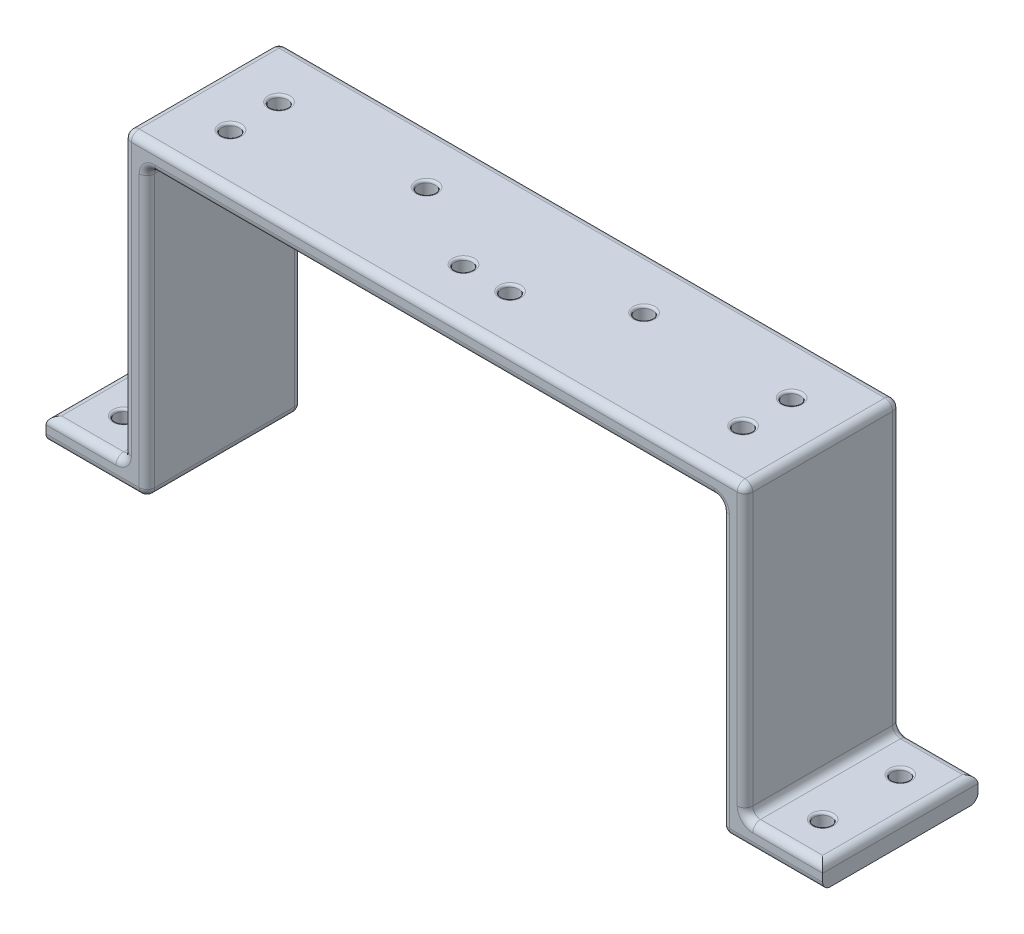
SolidWorks part; units mm, degrees
ref_plane "前视基准面" through (0, 0, 0) normal (0, 0, 1) x (1, 0, 0)
ref_plane "上视基准面" through (0, 0, 0) normal (0, 1, 0) x (1, 0, 0)
ref_plane "右视基准面" through (0, 0, 0) normal (1, 0, 0) x (0, 0, -1)
other "Configuration Table"
sketch "草图1" plane through (0, 0, 0) normal (0, 1, 0) x (1, 0, 0)
  line L0 (0, -55) -> (0, 55) construction
  line L1 (-5, 10) -> (5, 10)
  line L2 (-5, 10) -> (-5, -10)
  line L3 (-5, -10) -> (5, -10)
  line L4 (5, 10) -> (5, -10)
  line L5 (-55, 0) -> (55, 0) construction
  dimension "D1" = 20
  dimension "D2" = 10
  dimension "D3" = 5
  dimension "D4" = 10
extrude "凸台-拉伸1" add sketch "草图1" along normal blind 3
hole_wizard "Ø2.2 (2.2) Diameter Hole2" positions "草图2" profile "草图3" hole size "Ø2.2" standard "ANSI Metric" end condition up to next
sketch "草图2" plane through (0, 3, 0) normal (0, 1, 0) x (1, 0, 0)
  line L0 (0, -1.65) -> (0, 1.65) construction
  line L1 (5, 10) -> (-5, 10) construction
  point P0 (0, 5)
  point P4 (0, -5)
  dimension "D1" = 5
  dimension "D2" = 10
sketch "草图3" plane through (0, 3, -5) normal (1, 0, 0) x (0, 0, 1)
  line L0 (0, 0) -> (0, 3)
  line L1 (0, 3) -> (1.1, 3)
  line L2 (1.1, 3) -> (1.1, 0)
  line L5 (1.1, 0) -> (0, 0)
  line L11 (0, -6.35) -> (0, 107.95) construction
  dimension "通孔孔直径" = 2.2
  dimension "通孔孔深度" = 3
sketch "草图5" plane through (5, 0, 0) normal (1, 0, 0) x (0, 0, -1)
  line L1 (-10, 0) -> (10, 0)
  line L2 (-10, 0) -> (-10, 40)
  line L3 (-10, 40) -> (10, 40)
  line L4 (10, 0) -> (10, 40)
  dimension "D1" = 40
  dimension "D2" = 20
extrude "凸台-拉伸2" add sketch "草图5" along normal blind 80
ref_plane "基准面1" through (45, 0, 0) normal (-1, 0, 0) x (0, 0, 1)
mirror "镜向1" about plane through (45, 0, 0) normal (-1, 0, 0) of "Ø2.2 (2.2) Diameter Hole2", "凸台-拉伸1"
sketch "草图6" plane through (0, 0, 10) normal (0, 0, 1) x (1, 0, 0)
  line L0 (5.5, 0) -> (-5.5, 0) construction
  line L1 (8, 0) -> (82, 0)
  line L2 (8, 0) -> (8, 37)
  line L3 (8, 37) -> (82, 37)
  line L4 (82, 0) -> (82, 37)
  line L5 (5, 40) -> (5, 3) construction
  line L6 (85, 40) -> (85, 3) construction
  line L7 (85, 40) -> (5, 40) construction
  dimension "D1" = 3
  dimension "D2" = 3
  dimension "D3" = 3
extrude "切除-拉伸1" cut sketch "草图6" against normal up to next
hole_wizard "Ø2.2 (2.2) Diameter Hole3" positions "草图9" profile "草图10" hole size "Ø2.2" standard "ANSI Metric" end condition up to next
sketch "草图9" plane through (0, 40, 0) normal (0, 1, 0) x (1, 0, 0)
  line L0 (85, -10) -> (5, -10) construction
  line L1 (5, -10) -> (5, 10) construction
  line L3 (85, 10) -> (85, -10) construction
  line L4 (5, 10) -> (5, -10) construction
  point P13 (12, -3.25)
  point P15 (78, -3.25)
  point P26 (48, -3.25)
  point P29 (42, -3.25)
  point P32 (78, 3)
  point P35 (12, 3)
  point P37 (31, 3)
  point P39 (59, 3)
  dimension "D1" = 6.75
  dimension "D2" = 7
  dimension "D3" = 6.75
  dimension "D4" = 7
  dimension "D5" = 30
  dimension "D6" = 30
  dimension "D7" = 6.75
  dimension "D8" = 6.75
  dimension "D9" = 13
  dimension "D10" = 13
  dimension "D11" = 7
  dimension "D12" = 7
  dimension "D13" = 19
  dimension "D14" = 13
  dimension "D15" = 13
  dimension "D16" = 19
sketch "草图10" plane through (12, 40, 3.25) normal (1, 0, 0) x (0, 0, 1)
  line L0 (0, 0) -> (0, 3)
  line L1 (0, 3) -> (1.1, 3)
  line L2 (1.1, 3) -> (1.1, 0)
  line L5 (1.1, 0) -> (0, 0)
  line L11 (0, -6.35) -> (0, 107.95) construction
  dimension "通孔孔直径" = 2.2
  dimension "通孔孔深度" = 3
fillet "圆角1" radius 1 30 edges at (82, 18.5, -10) (0, 3, 10) (8, 37, 0) (82, 37, 0) (82, 0, 0) (88.5, 0, -10) (1.5, 0, -10) (8, 18.5, -10) (45, 37, -10) (5, 21.5, -10) (5, 3, 0) (45, 40, -10) (85, 40, 0) (85, 21.5, -10) (90, 3, -10) (90, 3, 10) (85, 3, 0) (95, 3, 0) (85, 21.5, 10) (88.5, 0, 10) (82, 18.5, 10) (8, 0, 0) (1.5, 0, 10) (0, 3, -10) (-5, 3, 0) (8, 18.5, 10) (45, 37, 10) (45, 40, 10) (5, 40, 0) (5, 21.5, 10)
fillet "圆角2" radius 0.3 24 edges at (90, 3, -3.9) (90, 3, 6.1) (90, 0, -3.9) (90, 0, 6.1) (0, 0, 6.1) (0, 3, 6.1) (0, 0, -3.9) (0, 3, -3.9) (12, 37, -1.9) (12, 37, 4.35) (31, 37, -1.9) (42, 37, 4.35) (78, 40, 4.35) (78, 37, -1.9) (59, 37, -1.9) (48, 37, 4.35) (78, 37, 4.35) (78, 40, -1.9) (59, 40, -1.9) (48, 40, 4.35) (42, 40, 4.35) (31, 40, -1.9) (12, 40, 4.35) (12, 40, -1.9)
